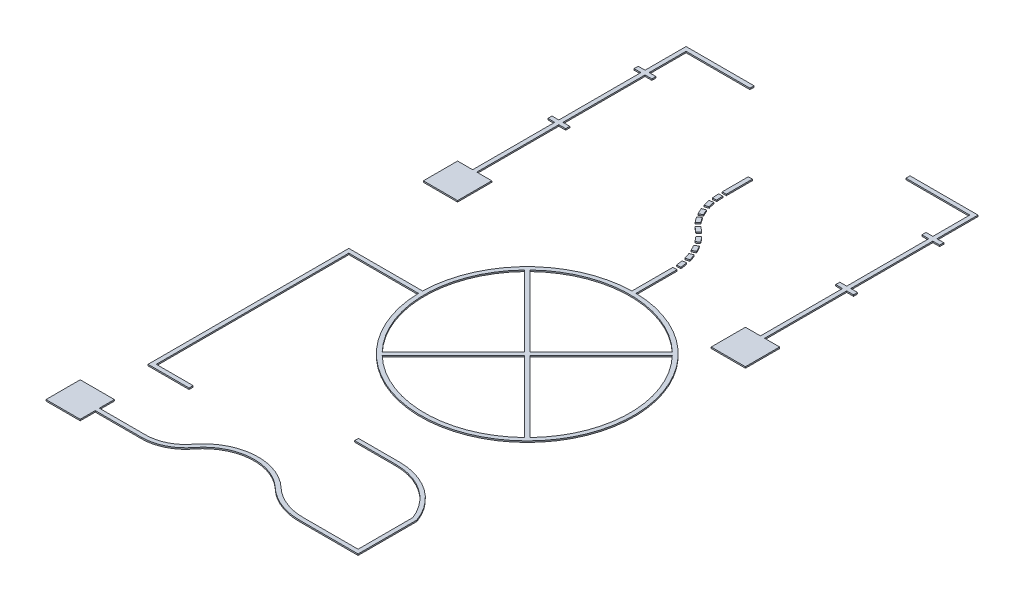
SolidWorks part; units mm, degrees
ref_plane "Front Plane" through (0, 0, 0) normal (0, 0, 1) x (1, 0, 0)
ref_plane "Top Plane" through (0, 0, 0) normal (0, 1, 0) x (1, 0, 0)
ref_plane "Right Plane" through (0, 0, 0) normal (1, 0, 0) x (0, 0, -1)
sketch "Sketch1" plane through (0, 0, 0) normal (0, 1, 0) x (1, 0, 0)
  line L1 (1219.2, -2438.4) -> (-1219.2, -2438.4)
  line L2 (1219.2, -2438.4) -> (1219.2, 2438.4)
  line L3 (1219.2, 2438.4) -> (-1219.2, 2438.4)
  line L4 (-1219.2, -2438.4) -> (-1219.2, 2438.4)
  line L5 (1219.2, -2438.4) -> (-1219.2, 2438.4) construction
  line L6 (1219.2, 2438.4) -> (-1219.2, -2438.4) construction
  point P0 (0, 0)
  dimension "D1" = 4876.8
  dimension "D2" = 2438.4
extrude "Boss-Extrude1" add sketch "Sketch1" along normal blind 100
sketch "Sketch2" plane through (0, 100, 0) normal (0, 1, 0) x (1, 0, 0)
  line L0 (-1219.2, 2438.4) -> (-1219.2, -2438.4) construction
  line L5 (-919.2, -2338.4) -> (-1169.2, -2088.4) construction
  line L6 (-919.2, -2088.4) -> (-1169.2, -2338.4) construction
  line L7 (752.297, 2125.4) -> (1069.2, 2125.4)
  line L9 (-919.2, -2308.4) -> (-919.2, -2198.4)
  line L12 (518.6973, -2285.2674) -> (948.6973, -2285.2674)
  line L13 (518.6973, -2255.2674) -> (918.6973, -2255.2674)
  line L14 (918.6973, -2255.2674) -> (918.6973, -1855.2674)
  line L15 (948.6973, -2285.2674) -> (948.6973, -1855.2674)
  line L17 (518.6973, -1552.3889) -> (218.6973, -1552.3889)
  line L18 (218.6973, -1552.3889) -> (218.6973, -1580.5173)
  line L19 (218.6973, -1580.5173) -> (518.6973, -1580.5173)
  line L20 (-1019.2, -1938.4) -> (-719.2, -1938.4)
  line L21 (-719.2, -1938.4) -> (-719.2, -1908.4)
  line L22 (-719.2, -1908.4) -> (-989.2, -1908.4)
  line L23 (-989.2, -1908.4) -> (-989.2, -415)
  line L24 (-989.2, -415) -> (-479.8558, -415)
  line L25 (300, -400) -> (-1082.2018, -400) construction
  line L26 (-1019.2, -1938.4) -> (-1019.2, -385)
  line L27 (-1019.2, -385) -> (-479.8558, -385)
  line L28 (300, -400) -> (300, -1150) construction
  line L29 (300, -400) -> (830.3301, -930.3301) construction
  line L30 (819.6179, -940.8301) -> (300, -421.2121)
  line L31 (300, -400) -> (-230.3301, 130.3301) construction
  line L32 (840.8301, -919.6179) -> (321.2121, -400)
  line L33 (300, -400) -> (830.3301, 130.3301) construction
  line L34 (830.3301, 130.3301) -> (-230.3301, -930.3301) construction
  line L35 (-240.8301, -919.6179) -> (278.7879, -400)
  line L36 (840.8301, 119.6179) -> (321.2121, -400)
  line L37 (300, -378.7879) -> (819.6179, 140.8301)
  line L38 (278.7879, -400) -> (-240.8301, 119.6179)
  line L39 (300, -421.2121) -> (-219.6179, -940.8301)
  line L40 (300, -378.7879) -> (-219.6179, 140.8301)
  line L41 (300, -400) -> (300, 350) construction
  line L42 (300, 350) -> (300, 632.1211) construction
  line L43 (285, 379.8558) -> (285, 679.8558)
  line L44 (315, 379.8558) -> (315, 679.8558)
  line L45 (285, 679.8558) -> (315, 679.8558)
  line L47 (283.4854, 707.2433) -> (313.3638, 709.8558)
  line L48 (276.8899, 753.4856) -> (306.3073, 759.3304)
  line L49 (270.3336, 781.5256) -> (299.2927, 789.3304)
  line L50 (255.7416, 825.8982) -> (283.6807, 836.8045)
  line L51 (243.6288, 853.9382) -> (270.7213, 866.8045)
  line L52 (221.3238, 894.9789) -> (246.8572, 910.7139)
  line L53 (202.4819, 923.0189) -> (226.6982, 940.7139)
  line L54 (172.9117, 959.1776) -> (195.0611, 979.4001)
  line L55 (144.8258, 987.2176) -> (165.012, 1009.4001)
  line L57 (104.4289, 1065.1132) -> (81.255, 1046.0708)
  line L58 (77.2262, 1102.6314) -> (51.9232, 1086.5256)
  line L59 (64.2637, 1124.5744) -> (37.9461, 1110.1861)
  line L60 (16.6704, 1155.4) -> (44.5324, 1166.5062)
  line L61 (34.3337, 1195.4) -> (5.6734, 1186.5553)
  line L62 (23.3708, 1240.4268) -> (-6.1476, 1235.1065)
  line L63 (-10.1201, 1262.2983) -> (19.6866, 1265.6449)
  line L64 (-12.6825, 1312.2021) -> (17.3102, 1311.9261)
  line L65 (18.3921, 1337.3888) -> (17.294, 1337.4721)
  line L66 (-12.7, 1337.4721) -> (-12.7, 1508.4)
  line L67 (-12.7, 1508.4) -> (17.294, 1508.4)
  line L68 (17.294, 1508.4) -> (17.294, 1337.4721)
  line L69 (2.297, 1508.4) -> (2.297, 2375.9732) construction
  line L82 (1219.2, 2438.4) -> (-1219.2, 2438.4) construction
  line L83 (126.2742, 1040.9739) -> (108.6188, 1016.7287)
  line L96 (-1174.606, 315.4) -> (-924.606, 315.4)
  line L107 (17.294, 1337.4721) -> (-12.7, 1337.4721)
  line L108 (17.294, 1311.9263) -> (17.294, 1308.4)
  line L135 (-581.5716, -2338.4) -> (-919.2, -2338.4)
  line L136 (-581.5716, -2308.4) -> (-919.2, -2308.4)
  line L137 (-919.2, -2323.4) -> (-975.8041, -2323.4) construction
  line L138 (-919.2, -2338.4) -> (-919.2, -2448.4)
  line L139 (-919.2, -2448.4) -> (-1169.2, -2448.4)
  line L140 (-1169.2, -2448.4) -> (-1169.2, -2338.4)
  line L141 (-919.2, -2198.4) -> (-1169.2, -2198.4)
  line L142 (-1169.2, -2198.4) -> (-1169.2, -2338.4)
  line L143 (1054.2, 1825.4) -> (1054.2, 1777.7373) construction
  line L144 (1069.2, 1825.4) -> (1069.2, 2125.4)
  line L145 (1219.2, -2438.4) -> (1219.2, 2438.4) construction
  line L146 (752.297, 2095.4) -> (1039.2, 2095.4)
  line L147 (1039.2, 2095.4) -> (1039.2, 1825.4)
  line L148 (1069.2, 1825.4) -> (1119.2, 1825.4)
  line L149 (1119.2, 1825.4) -> (1119.2, 1795.4)
  line L150 (1119.2, 1795.4) -> (1069.2, 1795.4)
  line L151 (1069.2, 1795.4) -> (1069.2, 1195.4)
  line L152 (1069.2, 1195.4) -> (1119.2, 1195.4)
  line L153 (1119.2, 1195.4) -> (1119.2, 1165.4)
  line L154 (1119.2, 1165.4) -> (1069.2, 1165.4)
  line L155 (1069.2, 1165.4) -> (1069.2, 565.4)
  line L156 (1039.2, 1165.4) -> (1039.2, 565.4)
  line L157 (989.2, 1165.4) -> (1039.2, 1165.4)
  line L158 (989.2, 1195.4) -> (989.2, 1165.4)
  line L159 (1039.2, 1195.4) -> (989.2, 1195.4)
  line L160 (1039.2, 1795.4) -> (1039.2, 1195.4)
  line L161 (989.2, 1795.4) -> (1039.2, 1795.4)
  line L162 (989.2, 1825.4) -> (989.2, 1795.4)
  line L163 (1039.2, 1825.4) -> (989.2, 1825.4)
  line L164 (1069.2, 565.4) -> (1179.2, 565.4)
  line L165 (1179.2, 565.4) -> (1179.2, 315.4)
  line L166 (1179.2, 315.4) -> (929.2, 315.4)
  line L167 (929.2, 315.4) -> (929.2, 565.4)
  line L168 (929.2, 565.4) -> (1039.2, 565.4)
  line L169 (1054.2, 536.5062) -> (1054.2, 519.3581) construction
  line L170 (752.297, 2125.4) -> (592.297, 2125.4)
  line L171 (592.297, 2125.4) -> (592.297, 2095.4)
  line L172 (592.297, 2095.4) -> (752.297, 2095.4)
  line L173 (-1174.606, 565.4) -> (-1174.606, 315.4)
  line L174 (-1064.606, 565.4) -> (-1174.606, 565.4)
  line L175 (-924.606, 315.4) -> (-924.606, 565.4)
  line L176 (-924.606, 565.4) -> (-1034.606, 565.4)
  line L177 (-1034.606, 1165.4) -> (-1034.606, 565.4)
  line L178 (-1064.606, 1165.4) -> (-1064.606, 565.4)
  line L179 (-1114.606, 1165.4) -> (-1064.606, 1165.4)
  line L180 (-1114.606, 1195.4) -> (-1114.606, 1165.4)
  line L181 (-1064.606, 1195.4) -> (-1114.606, 1195.4)
  line L182 (-984.606, 1195.4) -> (-984.606, 1165.4)
  line L183 (-984.606, 1165.4) -> (-1034.606, 1165.4)
  line L184 (-1034.606, 1195.4) -> (-984.606, 1195.4)
  line L185 (-1064.606, 1795.4) -> (-1064.606, 1195.4)
  line L186 (-1034.606, 1795.4) -> (-1034.606, 1195.4)
  line L187 (-984.606, 1825.4) -> (-984.606, 1795.4)
  line L188 (-984.606, 1795.4) -> (-1034.606, 1795.4)
  line L189 (-1114.606, 1795.4) -> (-1064.606, 1795.4)
  line L190 (-1114.606, 1825.4) -> (-1114.606, 1795.4)
  line L191 (-1064.606, 1825.4) -> (-1114.606, 1825.4)
  line L192 (-1034.606, 1825.4) -> (-984.606, 1825.4)
  line L193 (-1034.606, 2095.4) -> (-1034.606, 1825.4)
  line L194 (-1064.606, 1825.4) -> (-1064.606, 2125.4)
  line L195 (-747.703, 2095.4) -> (-1034.606, 2095.4)
  line L196 (-747.703, 2125.4) -> (-1064.606, 2125.4)
  line L197 (-587.703, 2095.4) -> (-747.703, 2095.4)
  line L198 (-747.703, 2125.4) -> (-587.703, 2125.4)
  line L199 (-587.703, 2125.4) -> (-587.703, 2095.4)
  line L200 (-1219.2, -2438.4) -> (1219.2, -2438.4) construction
  arc A7 (918.6973, -1855.2674) -> (518.6973, -1580.5173) centre (518.6973, -2009.066) ccw
  arc A8 (948.6973, -1855.2674) -> (518.6973, -1552.3889) centre (518.6973, -2009.066) ccw
  arc A9 (840.8301, -919.6179) -> (840.8301, 119.6179) centre (300, -400) ccw
  arc A10 (-479.8558, -415) -> (315, 379.8558) centre (300, -400) ccw
  arc A11 (-240.8301, 119.6179) -> (-240.8301, -919.6179) centre (300, -400) ccw
  arc A12 (-219.6179, -940.8301) -> (819.6179, -940.8301) centre (300, -400) ccw
  arc A13 (819.6179, 140.8301) -> (-219.6179, 140.8301) centre (300, -400) ccw
  arc A14 (285, 379.8558) -> (-479.8558, -385) centre (300, -400) ccw
  arc A17 (-12.7, 1308.4) -> (-10.1201, 1262.2983) centre (400.4986, 1308.4) ccw
  arc A18 (17.294, 1308.4) -> (19.6866, 1265.6449) centre (400.4986, 1308.4) ccw
  arc A19 (270.3336, 781.5256) -> (255.7416, 825.8982) centre (-143.9653, 669.8681) ccw
  arc A20 (283.4854, 707.2433) -> (276.8899, 753.4856) centre (-143.9653, 669.8681) ccw
  arc A21 (313.3638, 709.8558) -> (306.3073, 759.3304) centre (-143.9653, 669.8681) ccw
  arc A22 (299.2927, 789.3304) -> (283.6807, 836.8045) centre (-143.9653, 669.8681) ccw
  arc A23 (270.7213, 866.8045) -> (246.8572, 910.7139) centre (-143.9653, 669.8681) ccw
  arc A24 (243.6288, 853.9382) -> (221.3238, 894.9789) centre (-143.9653, 669.8681) ccw
  arc A25 (226.6982, 940.7139) -> (195.0611, 979.4001) centre (-143.9653, 669.8681) ccw
  arc A26 (202.4819, 923.0189) -> (172.9117, 959.1776) centre (-143.9653, 669.8681) ccw
  arc A27 (144.8258, 987.2176) -> (108.6188, 1016.7287) centre (-143.9653, 669.8681) ccw
  arc A28 (165.012, 1009.4001) -> (126.2742, 1040.9739) centre (-143.9653, 669.8681) ccw
  arc A29 (51.9232, 1086.5256) -> (81.255, 1046.0708) centre (400.4986, 1308.4) ccw
  arc A30 (77.2262, 1102.6314) -> (104.4289, 1065.1132) centre (400.4986, 1308.4) ccw
  arc A31 (44.5324, 1166.5062) -> (64.2637, 1124.5744) centre (400.4986, 1308.4) ccw
  arc A32 (16.6704, 1155.4) -> (37.9461, 1110.1861) centre (400.4986, 1308.4) ccw
  arc A33 (23.3708, 1240.4268) -> (34.3337, 1195.4) centre (400.4986, 1308.4) ccw
  arc A34 (-6.1476, 1235.1065) -> (5.6734, 1186.5553) centre (400.4986, 1308.4) ccw
  arc A35 (17.3102, 1311.9261) -> (19.6866, 1265.6449) centre (400.4986, 1308.4) ccw
  arc A36 (-12.6825, 1312.2021) -> (-10.1201, 1262.2983) centre (400.4986, 1308.4) ccw
  arc A38 (77.2262, 1102.6314) -> (104.4289, 1065.1132) centre (400.4986, 1308.4) ccw
  arc A39 (51.9232, 1086.5256) -> (81.255, 1046.0708) centre (400.4986, 1308.4) ccw
  arc A40 (44.5324, 1166.5062) -> (64.2637, 1124.5744) centre (400.4986, 1308.4) ccw
  arc A41 (16.6704, 1155.4) -> (37.9461, 1110.1861) centre (400.4986, 1308.4) ccw
  arc A42 (23.3708, 1240.4268) -> (34.3337, 1195.4) centre (400.4986, 1308.4) ccw
  arc A43 (-6.1476, 1235.1065) -> (5.6734, 1186.5553) centre (400.4986, 1308.4) ccw
  arc A47 (-581.5716, -2338.4) -> (-325.3202, -2211.9393) centre (-581.5716, -2015.5444) ccw
  arc A48 (-581.5716, -2308.4) -> (-349.1313, -2193.6901) centre (-581.5716, -2015.5444) ccw
  arc A50 (226.6802, -2168.6023) -> (-325.3202, -2211.9393) centre (-29.8396, -2438.4) ccw
  arc A51 (226.6802, -2168.6023) -> (518.6973, -2285.2674) centre (518.6973, -1861.47) ccw
  arc A52 (247.3516, -2146.8609) -> (518.6973, -2255.2674) centre (518.6973, -1861.47) ccw
  arc A53 (247.3516, -2146.8609) -> (-349.1313, -2193.6901) centre (-29.8396, -2438.4) ccw
  point P0 (-1044.2, -2213.4)
  line M8 (-1219.2, 2438.4) -> (-1219.2, -2438.4)
  line M9 (-1219.2, -2438.4) -> (1219.2, -2438.4)
  line M10 (1219.2, -2438.4) -> (1219.2, 2438.4)
  line M11 (1219.2, 2438.4) -> (-1219.2, 2438.4)
  dimension "D12" = 423.7974
  dimension "D21" = 857.0975
  dimension "D28" = 1500
  dimension "D31" = 1560
  dimension "D1" = 250
  dimension "D2" = 250
  dimension "D14" = 30
  dimension "D17" = 30
  dimension "D18" = 400
  dimension "D19" = 430
  dimension "D20" = 400
  dimension "D22" = 400
  dimension "D23" = 300
  dimension "D24" = 300
  dimension "D25" = 270
  dimension "D26" = 30
  dimension "D27" = 125
  dimension "D29" = 300
  dimension "D30" = 400
  dimension "D32" = 15
  dimension "D33" = 15
  dimension "D34" = 100
  dimension "D35" = 45
  dimension "D36" = 15
  dimension "D37" = 45
  dimension "D38" = 15
  dimension "D39" = 15
  dimension "D40" = 15
  dimension "D41" = 1499.7
  dimension "D42" = 519.6179
  dimension "D43" = 45
  dimension "D44" = 15
  dimension "D45" = 15
  dimension "D46" = 15
  dimension "D47" = 15
  dimension "D48" = 1499.7
  dimension "D49" = 15
  dimension "D50" = 15
  dimension "D51" = 300
  dimension "D52" = 30
  dimension "D53" = 50
  dimension "D54" = 30
  dimension "D55" = 50
  dimension "D56" = 30
  dimension "D57" = 50
  dimension "D58" = 30
  dimension "D59" = 50
  dimension "D60" = 30
  dimension "D61" = 50
  dimension "D62" = 1221.497
  dimension "D63" = 50
  dimension "D64" = 40
  dimension "D65" = 50
  dimension "D66" = 40
  dimension "D67" = 50
  dimension "D68" = 40
  dimension "D69" = 50
  dimension "D70" = 40
  dimension "D71" = 200
  dimension "D72" = 29.994
  dimension "D73" = 150
  dimension "D74" = 30
  dimension "D75" = 750
  dimension "D78" = 930
  dimension "D86" = 313
  dimension "D98" = 30
  dimension "D99" = 30
  dimension "D100" = 15
  dimension "D101" = 125
  dimension "D102" = 250
  dimension "D103" = 50
  dimension "D104" = 125
  dimension "D105" = 50
  dimension "D106" = 30
  dimension "D107" = 600
  dimension "D108" = 150
  dimension "D109" = 30
  dimension "D110" = 50
  dimension "D111" = 50
  dimension "D112" = 600
  dimension "D113" = 15
  dimension "D114" = 250
  dimension "D115" = 590
  dimension "0.125" = 125
extrude "Cut-Extrude1" cut sketch "Sketch2" against normal up to surface (100 mm away) contours A53 A52 L13 L14 A7 L19 L18 L17 A8 L15 L12 A51 A50 A47 L135 L138 L140 L142 L141 L9 L136 A48 A36 L64 A35 A18 L63 A17 A34 L62 A33 L61 A32 L60 A31 L59 A28 L55 A27 L83 M9 M10 M11 M8 | L39 A12 L30 | L32 A9 L36 | L37 A13 L40 | L38 A11 L35
sketch "Sketch3" plane through (0, 100, 0) normal (0, 1, 0) x (1, 0, 0)
  line L0 (-1169.2, -2438.4) -> (-919.2, -2438.4)
  line L1 (-919.2, -2438.4) -> (-919.2, -2448.4)
  line L2 (-919.2, -2448.4) -> (-1169.2, -2448.4)
  line L3 (-1169.2, -2448.4) -> (-1169.2, -2438.4)
  line L4 (-919.2, -2198.4) -> (-1169.2, -2198.4) construction
  dimension "D1" = 250
extrude "Boss-Extrude2" add sketch "Sketch3" against normal up to surface (100 mm away) up to face at (-47.9446, 0, 2094.1265)
sketch "Sketch4" plane through (0, 0, 0) normal (0, -1, 0) x (1, 0, 0)
  line L2 (313.3638, -709.8558) -> (283.4854, -707.2433)
  line L3 (276.8899, -753.4856) -> (306.3073, -759.3304)
  line L4 (313.3638, -709.8558) -> (283.4854, -707.2433)
  line L5 (276.8899, -753.4856) -> (306.3073, -759.3304)
  line L6 (299.2927, -789.3304) -> (270.3336, -781.5256)
  line L7 (255.7416, -825.8982) -> (283.6807, -836.8045)
  line L8 (299.2927, -789.3304) -> (270.3336, -781.5256)
  line L9 (255.7416, -825.8982) -> (283.6807, -836.8045)
  line L10 (285, -379.8558) -> (285, -679.8558)
  line L11 (285, -679.8558) -> (315, -679.8558)
  line L12 (315, -679.8558) -> (315, -379.8558)
  line L13 (-479.8558, 415) -> (-989.2, 415)
  line L14 (-919.2, 2338.4) -> (-919.2, 2448.4)
  line L15 (-919.2, 2448.4) -> (-1169.2, 2448.4)
  line L16 (-1169.2, 2448.4) -> (-1169.2, 2198.4)
  line L17 (-1169.2, 2198.4) -> (-919.2, 2198.4)
  line L18 (-919.2, 2198.4) -> (-919.2, 2308.4)
  line L19 (-919.2, 2308.4) -> (-581.5716, 2308.4)
  line L20 (518.6973, 2255.2674) -> (918.6973, 2255.2674)
  line L21 (918.6973, 2255.2674) -> (918.6973, 1855.2674)
  line L22 (518.6973, 1580.5173) -> (218.6973, 1580.5173)
  line L23 (218.6973, 1580.5173) -> (218.6973, 1552.3889)
  line L24 (218.6973, 1552.3889) -> (518.6973, 1552.3889)
  line L25 (948.6973, 1855.2674) -> (948.6973, 2285.2674)
  line L26 (948.6973, 2285.2674) -> (518.6973, 2285.2674)
  line L27 (-581.5716, 2338.4) -> (-919.2, 2338.4)
  line L28 (-919.2, 2338.4) -> (-919.2, 2448.4)
  line L29 (-919.2, 2448.4) -> (-1169.2, 2448.4)
  line L30 (-1169.2, 2448.4) -> (-1169.2, 2198.4)
  line L31 (-1169.2, 2198.4) -> (-919.2, 2198.4)
  line L32 (-919.2, 2198.4) -> (-919.2, 2308.4)
  line L33 (-919.2, 2308.4) -> (-581.5716, 2308.4)
  line L34 (518.6973, 2255.2674) -> (918.6973, 2255.2674)
  line L35 (918.6973, 2255.2674) -> (918.6973, 1855.2674)
  line L36 (518.6973, 1580.5173) -> (218.6973, 1580.5173)
  line L37 (218.6973, 1580.5173) -> (218.6973, 1552.3889)
  line L38 (218.6973, 1552.3889) -> (518.6973, 1552.3889)
  line L39 (948.6973, 1855.2674) -> (948.6973, 2285.2674)
  line L40 (948.6973, 2285.2674) -> (518.6973, 2285.2674)
  line L41 (-581.5716, 2338.4) -> (-919.2, 2338.4)
  line L42 (-989.2, 415) -> (-989.2, 1908.4)
  line L43 (-989.2, 1908.4) -> (-719.2, 1908.4)
  line L44 (-719.2, 1908.4) -> (-719.2, 1938.4)
  line L45 (-719.2, 1938.4) -> (-1019.2, 1938.4)
  line L46 (-1019.2, 1938.4) -> (-1019.2, 385)
  line L47 (-1019.2, 385) -> (-479.8558, 385)
  line L48 (285, -379.8558) -> (285, -679.8558)
  line L49 (285, -679.8558) -> (315, -679.8558)
  line L50 (315, -679.8558) -> (315, -379.8558)
  line L51 (-479.8558, 415) -> (-989.2, 415)
  line L52 (-989.2, 415) -> (-989.2, 1908.4)
  line L53 (-989.2, 1908.4) -> (-719.2, 1908.4)
  line L54 (-719.2, 1908.4) -> (-719.2, 1938.4)
  line L55 (-719.2, 1938.4) -> (-1019.2, 1938.4)
  line L56 (-1019.2, 1938.4) -> (-1019.2, 385)
  line L57 (-1019.2, 385) -> (-479.8558, 385)
  line L58 (270.7213, -866.8045) -> (243.6288, -853.9382)
  line L59 (221.3238, -894.9789) -> (246.8572, -910.7139)
  line L60 (270.7213, -866.8045) -> (243.6288, -853.9382)
  line L61 (221.3238, -894.9789) -> (246.8572, -910.7139)
  line L62 (226.6982, -940.7139) -> (202.4819, -923.0189)
  line L63 (172.9117, -959.1776) -> (195.0611, -979.4001)
  line L64 (226.6982, -940.7139) -> (202.4819, -923.0189)
  line L65 (172.9117, -959.1776) -> (195.0611, -979.4001)
  line L66 (165.012, -1009.4001) -> (144.8258, -987.2176)
  line L67 (108.6188, -1016.7287) -> (126.2742, -1040.9739)
  line L68 (165.012, -1009.4001) -> (144.8258, -987.2176)
  line L69 (108.6188, -1016.7287) -> (126.2742, -1040.9739)
  line L70 (51.9232, -1086.5256) -> (77.2262, -1102.6314)
  line L71 (104.4289, -1065.1132) -> (81.255, -1046.0708)
  line L72 (51.9232, -1086.5256) -> (77.2262, -1102.6314)
  line L73 (104.4289, -1065.1132) -> (81.255, -1046.0708)
  line L74 (16.6704, -1155.4) -> (44.5324, -1166.5062)
  line L75 (64.2637, -1124.5744) -> (37.9461, -1110.1861)
  line L76 (16.6704, -1155.4) -> (44.5324, -1166.5062)
  line L77 (64.2637, -1124.5744) -> (37.9461, -1110.1861)
  line L78 (-6.1476, -1235.1065) -> (23.3708, -1240.4268)
  line L79 (34.3337, -1195.4) -> (5.6734, -1186.5553)
  line L80 (-6.1476, -1235.1065) -> (23.3708, -1240.4268)
  line L81 (34.3337, -1195.4) -> (5.6734, -1186.5553)
  line L82 (-12.6825, -1312.2021) -> (17.3102, -1311.9261)
  line L83 (19.6866, -1265.6449) -> (-10.1201, -1262.2983)
  line L84 (-12.6825, -1312.2021) -> (17.3102, -1311.9261)
  line L85 (19.6866, -1265.6449) -> (-10.1201, -1262.2983)
  line L88 (-12.7, -1508.4) -> (17.294, -1508.4)
  line L89 (17.294, -1508.4) -> (17.294, -1337.4721)
  line L90 (17.294, -1337.4721) -> (-12.7, -1337.4721)
  line L91 (-12.7, -1337.4721) -> (-12.7, -1508.4)
  line L92 (-12.7, -1508.4) -> (17.294, -1508.4)
  line L93 (17.294, -1508.4) -> (17.294, -1337.4721)
  line L94 (17.294, -1337.4721) -> (-12.7, -1337.4721)
  line L95 (-12.7, -1337.4721) -> (-12.7, -1508.4)
  line L118 (-1064.606, -1825.4) -> (-1064.606, -2125.4)
  line L119 (-1064.606, -2125.4) -> (-587.703, -2125.4)
  line L120 (-587.703, -2125.4) -> (-587.703, -2095.4)
  line L121 (-587.703, -2095.4) -> (-1034.606, -2095.4)
  line L122 (-1034.606, -2095.4) -> (-1034.606, -1825.4)
  line L123 (-1034.606, -1825.4) -> (-984.606, -1825.4)
  line L124 (-984.606, -1825.4) -> (-984.606, -1795.4)
  line L125 (-984.606, -1795.4) -> (-1034.606, -1795.4)
  line L126 (-1034.606, -1795.4) -> (-1034.606, -1195.4)
  line L127 (-1034.606, -1195.4) -> (-984.606, -1195.4)
  line L128 (-984.606, -1195.4) -> (-984.606, -1165.4)
  line L129 (-984.606, -1165.4) -> (-1034.606, -1165.4)
  line L130 (-1034.606, -1165.4) -> (-1034.606, -565.4)
  line L131 (-1034.606, -565.4) -> (-924.606, -565.4)
  line L132 (-924.606, -565.4) -> (-924.606, -315.4)
  line L133 (-924.606, -315.4) -> (-1174.606, -315.4)
  line L134 (-1174.606, -315.4) -> (-1174.606, -565.4)
  line L135 (-1174.606, -565.4) -> (-1064.606, -565.4)
  line L136 (-1064.606, -565.4) -> (-1064.606, -1165.4)
  line L137 (-1064.606, -1165.4) -> (-1114.606, -1165.4)
  line L138 (-1114.606, -1165.4) -> (-1114.606, -1195.4)
  line L139 (-1114.606, -1195.4) -> (-1064.606, -1195.4)
  line L140 (-1064.606, -1195.4) -> (-1064.606, -1795.4)
  line L141 (-1064.606, -1795.4) -> (-1114.606, -1795.4)
  line L142 (-1114.606, -1795.4) -> (-1114.606, -1825.4)
  line L143 (-1114.606, -1825.4) -> (-1064.606, -1825.4)
  line L144 (-1064.606, -1825.4) -> (-1064.606, -2125.4)
  line L145 (-1064.606, -2125.4) -> (-587.703, -2125.4)
  line L146 (-587.703, -2125.4) -> (-587.703, -2095.4)
  line L147 (-587.703, -2095.4) -> (-1034.606, -2095.4)
  line L148 (-1034.606, -2095.4) -> (-1034.606, -1825.4)
  line L149 (-1034.606, -1825.4) -> (-984.606, -1825.4)
  line L150 (-984.606, -1825.4) -> (-984.606, -1795.4)
  line L151 (-984.606, -1795.4) -> (-1034.606, -1795.4)
  line L152 (-1034.606, -1795.4) -> (-1034.606, -1195.4)
  line L153 (-1034.606, -1195.4) -> (-984.606, -1195.4)
  line L154 (-984.606, -1195.4) -> (-984.606, -1165.4)
  line L155 (-984.606, -1165.4) -> (-1034.606, -1165.4)
  line L156 (-1034.606, -1165.4) -> (-1034.606, -565.4)
  line L157 (-1034.606, -565.4) -> (-924.606, -565.4)
  line L158 (-924.606, -565.4) -> (-924.606, -315.4)
  line L159 (-924.606, -315.4) -> (-1174.606, -315.4)
  line L160 (-1174.606, -315.4) -> (-1174.606, -565.4)
  line L161 (-1174.606, -565.4) -> (-1064.606, -565.4)
  line L162 (-1064.606, -565.4) -> (-1064.606, -1165.4)
  line L163 (-1064.606, -1165.4) -> (-1114.606, -1165.4)
  line L164 (-1114.606, -1165.4) -> (-1114.606, -1195.4)
  line L165 (-1114.606, -1195.4) -> (-1064.606, -1195.4)
  line L166 (-1064.606, -1195.4) -> (-1064.606, -1795.4)
  line L167 (-1064.606, -1795.4) -> (-1114.606, -1795.4)
  line L168 (-1114.606, -1795.4) -> (-1114.606, -1825.4)
  line L169 (-1114.606, -1825.4) -> (-1064.606, -1825.4)
  line L170 (1039.2, -2095.4) -> (592.297, -2095.4)
  line L171 (592.297, -2095.4) -> (592.297, -2125.4)
  line L172 (592.297, -2125.4) -> (1069.2, -2125.4)
  line L173 (1069.2, -2125.4) -> (1069.2, -1825.4)
  line L174 (1069.2, -1825.4) -> (1119.2, -1825.4)
  line L175 (1119.2, -1825.4) -> (1119.2, -1795.4)
  line L176 (1119.2, -1795.4) -> (1069.2, -1795.4)
  line L177 (1069.2, -1795.4) -> (1069.2, -1195.4)
  line L178 (1069.2, -1195.4) -> (1119.2, -1195.4)
  line L179 (1119.2, -1195.4) -> (1119.2, -1165.4)
  line L180 (1119.2, -1165.4) -> (1069.2, -1165.4)
  line L181 (1069.2, -1165.4) -> (1069.2, -565.4)
  line L182 (1069.2, -565.4) -> (1179.2, -565.4)
  line L183 (1179.2, -565.4) -> (1179.2, -315.4)
  line L184 (1179.2, -315.4) -> (929.2, -315.4)
  line L185 (929.2, -315.4) -> (929.2, -565.4)
  line L186 (929.2, -565.4) -> (1039.2, -565.4)
  line L187 (1039.2, -565.4) -> (1039.2, -1165.4)
  line L188 (1039.2, -1165.4) -> (989.2, -1165.4)
  line L189 (989.2, -1165.4) -> (989.2, -1195.4)
  line L190 (989.2, -1195.4) -> (1039.2, -1195.4)
  line L191 (1039.2, -1195.4) -> (1039.2, -1795.4)
  line L192 (1039.2, -1795.4) -> (989.2, -1795.4)
  line L193 (989.2, -1795.4) -> (989.2, -1825.4)
  line L194 (989.2, -1825.4) -> (1039.2, -1825.4)
  line L195 (1039.2, -1825.4) -> (1039.2, -2095.4)
  line L196 (1039.2, -2095.4) -> (592.297, -2095.4)
  line L197 (592.297, -2095.4) -> (592.297, -2125.4)
  line L198 (592.297, -2125.4) -> (1069.2, -2125.4)
  line L199 (1069.2, -2125.4) -> (1069.2, -1825.4)
  line L200 (1069.2, -1825.4) -> (1119.2, -1825.4)
  line L201 (1119.2, -1825.4) -> (1119.2, -1795.4)
  line L202 (1119.2, -1795.4) -> (1069.2, -1795.4)
  line L203 (1069.2, -1795.4) -> (1069.2, -1195.4)
  line L204 (1069.2, -1195.4) -> (1119.2, -1195.4)
  line L205 (1119.2, -1195.4) -> (1119.2, -1165.4)
  line L206 (1119.2, -1165.4) -> (1069.2, -1165.4)
  line L207 (1069.2, -1165.4) -> (1069.2, -565.4)
  line L208 (1069.2, -565.4) -> (1179.2, -565.4)
  line L209 (1179.2, -565.4) -> (1179.2, -315.4)
  line L210 (1179.2, -315.4) -> (929.2, -315.4)
  line L211 (929.2, -315.4) -> (929.2, -565.4)
  line L212 (929.2, -565.4) -> (1039.2, -565.4)
  line L213 (1039.2, -565.4) -> (1039.2, -1165.4)
  line L214 (1039.2, -1165.4) -> (989.2, -1165.4)
  line L215 (989.2, -1165.4) -> (989.2, -1195.4)
  line L216 (989.2, -1195.4) -> (1039.2, -1195.4)
  line L217 (1039.2, -1195.4) -> (1039.2, -1795.4)
  line L218 (1039.2, -1795.4) -> (989.2, -1795.4)
  line L219 (989.2, -1795.4) -> (989.2, -1825.4)
  line L220 (989.2, -1825.4) -> (1039.2, -1825.4)
  line L221 (1039.2, -1825.4) -> (1039.2, -2095.4)
  arc A2 (-479.8558, 385) -> (285, -379.8558) centre (300, 400) ccw
  arc A3 (315, -379.8558) -> (-479.8558, 415) centre (300, 400) ccw
  arc A4 (-479.8558, 385) -> (285, -379.8558) centre (300, 400) ccw
  arc A5 (315, -379.8558) -> (-479.8558, 415) centre (300, 400) ccw
  arc A6 (306.3073, -759.3304) -> (313.3638, -709.8558) centre (-143.9653, -669.8681) ccw
  arc A7 (276.8899, -753.4856) -> (283.4854, -707.2433) centre (-143.9653, -669.8681) ccw
  arc A8 (-349.1313, 2193.6901) -> (-581.5716, 2308.4) centre (-581.5716, 2015.5444) ccw
  arc A9 (-349.1313, 2193.6901) -> (247.3516, 2146.8609) centre (-29.8396, 2438.4) ccw
  arc A10 (518.6973, 2255.2674) -> (247.3516, 2146.8609) centre (518.6973, 1861.47) ccw
  arc A11 (518.6973, 1580.5173) -> (918.6973, 1855.2674) centre (518.6973, 2009.066) ccw
  arc A12 (518.6973, 1552.3889) -> (948.6973, 1855.2674) centre (518.6973, 2009.066) ccw
  arc A13 (518.6973, 2285.2674) -> (226.6802, 2168.6023) centre (518.6973, 1861.47) ccw
  arc A14 (-325.3202, 2211.9393) -> (226.6802, 2168.6023) centre (-29.8396, 2438.4) ccw
  arc A15 (-325.3202, 2211.9393) -> (-581.5716, 2338.4) centre (-581.5716, 2015.5444) ccw
  arc A16 (-349.1313, 2193.6901) -> (-581.5716, 2308.4) centre (-581.5716, 2015.5444) ccw
  arc A17 (-349.1313, 2193.6901) -> (247.3516, 2146.8609) centre (-29.8396, 2438.4) ccw
  arc A18 (518.6973, 2255.2674) -> (247.3516, 2146.8609) centre (518.6973, 1861.47) ccw
  arc A19 (518.6973, 1580.5173) -> (918.6973, 1855.2674) centre (518.6973, 2009.066) ccw
  arc A20 (518.6973, 1552.3889) -> (948.6973, 1855.2674) centre (518.6973, 2009.066) ccw
  arc A21 (518.6973, 2285.2674) -> (226.6802, 2168.6023) centre (518.6973, 1861.47) ccw
  arc A22 (-325.3202, 2211.9393) -> (226.6802, 2168.6023) centre (-29.8396, 2438.4) ccw
  arc A23 (-325.3202, 2211.9393) -> (-581.5716, 2338.4) centre (-581.5716, 2015.5444) ccw
  arc A24 (306.3073, -759.3304) -> (313.3638, -709.8558) centre (-143.9653, -669.8681) ccw
  arc A25 (276.8899, -753.4856) -> (283.4854, -707.2433) centre (-143.9653, -669.8681) ccw
  arc A26 (283.6807, -836.8045) -> (299.2927, -789.3304) centre (-143.9653, -669.8681) ccw
  arc A27 (255.7416, -825.8982) -> (270.3336, -781.5256) centre (-143.9653, -669.8681) ccw
  arc A28 (283.6807, -836.8045) -> (299.2927, -789.3304) centre (-143.9653, -669.8681) ccw
  arc A29 (255.7416, -825.8982) -> (270.3336, -781.5256) centre (-143.9653, -669.8681) ccw
  arc A30 (221.3238, -894.9789) -> (243.6288, -853.9382) centre (-143.9653, -669.8681) ccw
  arc A31 (246.8572, -910.7139) -> (270.7213, -866.8045) centre (-143.9653, -669.8681) ccw
  arc A32 (221.3238, -894.9789) -> (243.6288, -853.9382) centre (-143.9653, -669.8681) ccw
  arc A33 (246.8572, -910.7139) -> (270.7213, -866.8045) centre (-143.9653, -669.8681) ccw
  arc A34 (172.9117, -959.1776) -> (202.4819, -923.0189) centre (-143.9653, -669.8681) ccw
  arc A35 (195.0611, -979.4001) -> (226.6982, -940.7139) centre (-143.9653, -669.8681) ccw
  arc A36 (172.9117, -959.1776) -> (202.4819, -923.0189) centre (-143.9653, -669.8681) ccw
  arc A37 (195.0611, -979.4001) -> (226.6982, -940.7139) centre (-143.9653, -669.8681) ccw
  arc A38 (126.2742, -1040.9739) -> (165.012, -1009.4001) centre (-143.9653, -669.8681) ccw
  arc A39 (108.6188, -1016.7287) -> (144.8258, -987.2176) centre (-143.9653, -669.8681) ccw
  arc A40 (126.2742, -1040.9739) -> (165.012, -1009.4001) centre (-143.9653, -669.8681) ccw
  arc A41 (108.6188, -1016.7287) -> (144.8258, -987.2176) centre (-143.9653, -669.8681) ccw
  arc A42 (104.4289, -1065.1132) -> (77.2262, -1102.6314) centre (400.4986, -1308.4) ccw
  arc A43 (81.255, -1046.0708) -> (51.9232, -1086.5256) centre (400.4986, -1308.4) ccw
  arc A44 (104.4289, -1065.1132) -> (77.2262, -1102.6314) centre (400.4986, -1308.4) ccw
  arc A45 (81.255, -1046.0708) -> (51.9232, -1086.5256) centre (400.4986, -1308.4) ccw
  arc A46 (37.9461, -1110.1861) -> (16.6704, -1155.4) centre (400.4986, -1308.4) ccw
  arc A47 (64.2637, -1124.5744) -> (44.5324, -1166.5062) centre (400.4986, -1308.4) ccw
  arc A48 (37.9461, -1110.1861) -> (16.6704, -1155.4) centre (400.4986, -1308.4) ccw
  arc A49 (64.2637, -1124.5744) -> (44.5324, -1166.5062) centre (400.4986, -1308.4) ccw
  arc A50 (5.6734, -1186.5553) -> (-6.1476, -1235.1065) centre (400.4986, -1308.4) ccw
  arc A51 (34.3337, -1195.4) -> (23.3708, -1240.4268) centre (400.4986, -1308.4) ccw
  arc A52 (5.6734, -1186.5553) -> (-6.1476, -1235.1065) centre (400.4986, -1308.4) ccw
  arc A53 (34.3337, -1195.4) -> (23.3708, -1240.4268) centre (400.4986, -1308.4) ccw
  arc A54 (-10.1201, -1262.2983) -> (-12.6825, -1312.2021) centre (400.4986, -1308.4) ccw
  arc A55 (19.6866, -1265.6449) -> (17.3102, -1311.9261) centre (400.4986, -1308.4) ccw
  arc A56 (-10.1201, -1262.2983) -> (-12.6825, -1312.2021) centre (400.4986, -1308.4) ccw
  arc A57 (19.6866, -1265.6449) -> (17.3102, -1311.9261) centre (400.4986, -1308.4) ccw
  dimension "D1" = 0
  dimension "D2" = 0
  dimension "D3" = 0
  dimension "D4" = 0
  dimension "D5" = 0
  dimension "D6" = 0
  dimension "D7" = 0
  dimension "D8" = 0
  dimension "D9" = 0
  dimension "D10" = 0
  dimension "D11" = 0
  dimension "D12" = 0
  dimension "D13" = 0
  dimension "D14" = 0
extrude "Cut-Extrude2" cut sketch "Sketch4" against normal offset from surface (90 mm away) 10 up to face at (-1014.075, 100, -1356.1692)
sketch "Sketch5" plane through (0, 100, 0) normal (0, 1, 0) x (1, 0, 0)
  line L0 (-1019.2, -1852.5) -> (-719.2, -1852.5)
  line L1 (-1019.2, -1938.4) -> (-1019.2, -385) construction
  line L2 (-719.2, -1852.5) -> (-719.2, -1822.5)
  line L3 (-719.2, -1822.5) -> (-1019.2, -1822.5)
  line L4 (-1019.2, -1938.4) -> (-719.2, -1938.4) construction
  line L5 (-1019.2, -1822.5) -> (-1019.2, -1852.5)
  dimension "D1" = 85.9
  dimension "D2" = 85.9
  dimension "D3" = 30
extrude "Boss-Extrude4" add sketch "Sketch5" against normal blind 10
sketch "Sketch7" plane through (0, 100, 0) normal (0, 1, 0) x (1, 0, 0)
  line L0 (-719.2, -1852.5) -> (-1019.2, -1852.5)
  line L1 (-1019.2, -1938.4) -> (-1019.2, -385) construction
  line L2 (-1019.2, -1852.5) -> (-1019.2, -1938.4)
  line L3 (-1019.2, -1938.4) -> (-719.2, -1938.4)
  line L4 (-719.2, -1938.4) -> (-719.2, -1852.5)
extrude "Cut-Extrude4" cut sketch "Sketch7" against normal blind 10
sketch "Sketch8" plane through (0, 0, -1508.4) normal (0, 0, -1) x (-1, 0, 0)
  line L4 (-17.294, 100) -> (-17.294, 90)
  line L5 (-17.294, 90) -> (12.7, 90)
  line L6 (12.7, 90) -> (12.7, 100)
  line L7 (12.7, 100) -> (-17.294, 100)
  line L8 (-17.294, 100) -> (-17.294, 90)
  line L9 (-17.294, 90) -> (12.7, 90)
  line L10 (12.7, 90) -> (12.7, 100)
  line L11 (12.7, 100) -> (-17.294, 100)
  dimension "D1" = 0
extrude "Boss-Extrude5" add sketch "Sketch8" along normal blind 20
sketch "Sketch9" plane through (592.297, 0, 0) normal (-1, 0, 0) x (0, 0, 1)
  line L4 (-2125.4, 90) -> (-2095.4, 90)
  line L5 (-2095.4, 90) -> (-2095.4, 100)
  line L6 (-2095.4, 100) -> (-2125.4, 100)
  line L7 (-2125.4, 100) -> (-2125.4, 90)
  line L8 (-2125.4, 90) -> (-2095.4, 90)
  line L9 (-2095.4, 90) -> (-2095.4, 100)
  line L10 (-2095.4, 100) -> (-2125.4, 100)
  line L11 (-2125.4, 100) -> (-2125.4, 90)
  dimension "D1" = 0
extrude "Boss-Extrude6" add sketch "Sketch9" along normal blind 20
sketch "Sketch10" plane through (-587.703, 0, 0) normal (1, 0, 0) x (0, 0, -1)
  line L4 (2095.4, 100) -> (2095.4, 90)
  line L5 (2095.4, 90) -> (2125.4, 90)
  line L6 (2125.4, 90) -> (2125.4, 100)
  line L7 (2125.4, 100) -> (2095.4, 100)
  line L8 (2095.4, 100) -> (2095.4, 90)
  line L9 (2095.4, 90) -> (2125.4, 90)
  line L10 (2125.4, 90) -> (2125.4, 100)
  line L11 (2125.4, 100) -> (2095.4, 100)
  dimension "D1" = 0
extrude "Boss-Extrude7" add sketch "Sketch10" along normal blind 20
